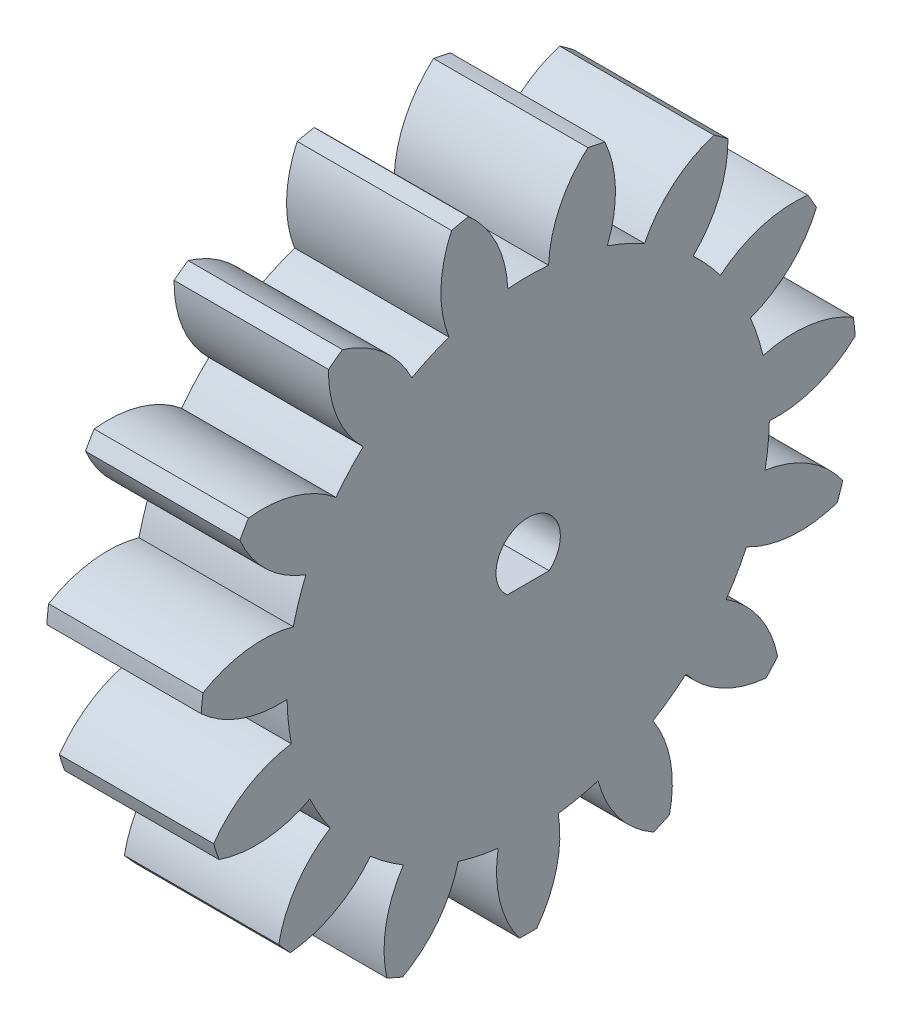
SolidWorks part; units mm, degrees
ref_plane "Plane1" through (0, 0, 0) normal (0, 0, 1) x (1, 0, 0)
ref_plane "Plane2" through (0, 0, 0) normal (0, 1, 0) x (1, 0, 0)
ref_plane "Plane3" through (0, 0, 0) normal (1, 0, 0) x (0, 0, -1)
other "Configuration Table"
sketch "HoldingSke" plane through (0, 0, 0) normal (0, 1, 0) x (1, 0, 0)
  line L0 (0, 0) -> (0.322, -0.0863)
  line L1 (-15, 0) -> (100, 0) construction
  line L2 (0, 0) -> (-2.1039, 2.3779)
  line L3 (0, 0) -> (-11.863, 4.5341)
  line L4 (0, 0) -> (8.3417, 2.2352)
  line L5 (0, 0) -> (-46.8476, -17.4728)
  line L6 (0, 0) -> (-9.9476, -6.7116)
  line L7 (-2.1039, 2.3779) -> (8.6586, 51.2059)
  line L8 (-76.2, 54.61) -> (-76.1, 54.61)
  line L9 (-71.009, 38.7566) -> (-53.1078, 45.2721)
  line L10 (-76.2, 71.12) -> (104.1128, 71.12)
  line L11 (0, 0) -> (-12, 0)
  line L12 (-76.2, 101.6) -> (-76.093, 101.6)
  line L13 (24.9733, 27.94) -> (52.9518, 28.4284)
  line L14 (24.9733, 27.94) -> (24.9743, 27.94)
  line L15 (24.9733, 27.94) -> (100.4006, 29.5858)
  line L16 (-63.627, -3) -> (-12.827, -3)
  circle A0 centre (0, 0) radius 0.4
  circle A1 centre (0, 0) radius 18.749
  circle A2 centre (0, 0) radius 37.5
  circle A3 centre (0, 0) radius 0.4
  dimension "MHD" = 37.498
  dimension "Hub_dia" = 75
  dimension "Bore" = 0.8
  dimension "MBD" = 0.8
  dimension "Num_teeth" = 15
  dimension "Pitch" = 0.3333
  dimension "Overall_len" = 50
  dimension "Show_teeth" = 15
  dimension "Thickness" = 12
  dimension "OAL" = 50.0001
  dimension "T_dim" = 0.1
  dimension "Ap" = 20
  dimension "H" = 19.05
  dimension "Pitch_radius" = 180.3128
  dimension "Width" = 12
  dimension "Backlash" = 0.107
  dimension "Addendum_fac" = 1
  dimension "Dedendum_fac" = 1.25
  dimension "Clearance_fac" = 0.25
  dimension "Dedendum_add" = 0.001
  dimension "Module" = 3
sketch "BasProSke" plane through (0, 0, 0) normal (0, 1, 0) x (1, 0, 0)
  line L0 (-10, 0) -> (60, 0) construction
  line L1 (0, 0) -> (0, 25.5)
  line L2 (0, 0) -> (12, 0)
  line L3 (12, 0) -> (12, 25.5)
  line L4 (12, 25.5) -> (0, 25.5)
  dimension "Thickness" = 12
  dimension "Diameter" = 51
revolve "Base-Revolve" add sketch "BasProSke" angle 360 about L0
sketch "TooCutSke" plane through (0, 0, 0) normal (1, 0, 0) x (0, 0, -1)
  line L1 (0, 0) -> (0, 107) construction
  line L2 (0, 0) -> (-2.539, 22.3563) construction
  line L3 (0, 0) -> (-9.3126, 43.8125) construction
  line L4 (-2.539, 22.3563) -> (-4.6563, 21.9062) construction
  arc A0 (1.5846, 18.6819) -> (-1.5846, 18.6819) centre (0, 0) ccw
  arc A1 (4.6669, 25.0951) -> (-4.6669, 25.0951) centre (0, 0) ccw
  circle A2 centre (0, 0) radius 22.5 construction
  circle A3 centre (0, 0) radius 21.1431 construction
  arc A4 (-1.5846, 18.6819) -> (-4.6669, 25.0951) centre (-10.5768, 18.3074) ccw
  arc A5 (4.6669, 25.0951) -> (1.5846, 18.6819) centre (10.5768, 18.3074) ccw
  dimension "Root_dia" = 37.498
  dimension "Overcut_dia" = 51.0508
  dimension "Pitch_dia" = 45
  dimension "Base_dia" = 42.2862
  dimension "Flank_rad" = 9
  dimension "Half_ang" = 12
  dimension "Half_CT" = 2.1646
extrude "ToothCut" cut sketch "TooCutSke" along normal through all
fillet "Breaks" [suppressed] radius 0.06
fillet "RootFillets" [suppressed] radius 0.751
pattern_circular "TeethCuts" count 15 every 24 about axis through (-10, 0, 0) along (1, 0, 0) of "ToothCut", "RootFillets", "Breaks"
sketch "HubNeaOneSke" plane through (0, 0, 0) normal (-1, 0, 0) x (0, 0, 1)
  circle A0 centre (0, 0) radius 18.749
  dimension "Diameter" = 37.498
extrude "HubNearOne" [suppressed] add sketch "HubNeaOneSke" along normal blind 38.0001
sketch "HubNeaBotSke" plane through (0, 0, 0) normal (-1, 0, 0) x (0, 0, 1)
  circle A0 centre (0, 0) radius 18.749
  dimension "Diameter" = 37.498
extrude "HubNearBoth" [suppressed] add sketch "HubNeaBotSke" along normal blind 19
ref_plane "FarPln" through (12, 0, 0) normal (1, 0, 0) x (0, 0, -1)
sketch "HubFarSke" plane through (12, 0, 0) normal (1, 0, 0) x (0, 0, -1)
  circle A0 centre (0, 0) radius 18.749
  dimension "Diameter" = 37.498
extrude "HubFar" [suppressed] add sketch "HubFarSke" along normal blind 19
sketch "BorSke" plane through (0, 0, 0) normal (1, 0, 0) x (0, 0, -1)
  circle A0 centre (0, 0) radius 0.4
  dimension "Diameter" = 0.8
extrude "Bore" cut sketch "BorSke" along normal mid plane 100.0001
sketch "KeySke" plane through (0, 0, 0) normal (1, 0, 0) x (0, 0, -1)
  line L0 (-0.05, 0) -> (-0.05, 0.5)
  line L1 (-0.05, 0.5) -> (0.05, 0.5)
  line L2 (0.05, 0.5) -> (0.05, 0)
  line L3 (0, 0) -> (0, 34) construction
  line L4 (-0.05, 0) -> (0.05, 0)
  dimension "Offset" = 0.5
  dimension "Width" = 0.1
extrude "Keyway" [suppressed] cut sketch "KeySke" along normal mid plane 100.0001
pattern_circular "Keyway2" [suppressed] count 2 every 90 about axis through (-10, 0, 0) along (1, 0, 0)
sketch "Sketch1" plane through (12, 0, 0) normal (1, 0, 0) x (0, 0, -1)
  line L0 (-3.7168, 2.5) -> (6.744, 2.5) construction
  line L1 (-4.4327, -1.9) -> (4.1469, -1.9)
  circle A0 centre (0, 0) radius 2.5
  dimension "D1" = 5
  dimension "D2" = 4.4
extrude "Cut-Extrude1" cut sketch "Sketch1" against normal through all both and the other way through all contours L1 A0
equation "' \"Module@HoldingSke\" = 6.35"
equation "' \"Num_teeth@HoldingSke\" = 12"
equation "' \"Ap@HoldingSke\" =  20"
equation "' \"Ap@HoldingSke\" = 20"
equation "' \"Width@HoldingSke\" = 0.5 * 25.4"
equation "' \"Hub_dia@HoldingSke\"= 1 * 25.4"
equation "' \"Hub_dia@HoldingSke\" = 1 * 25.4"
equation "' \"Overall_len@HoldingSke\" = 1.0 * 25.4"
equation "' \"Bore@HoldingSke\" = 0.75 * 25.4"
equation "' \"T_dim@HoldingSke\" = 0.1 * 25.4"
equation "' \"Width@KeySke\" = 0.25 * 25.4"
equation "' \"Show_teeth@HoldingSke\" = 13"
equation "' \"Backlash@HoldingSke\" = 0.009 * 25.4"
equation "' \"Addendum_fac@HoldingSke\" = 1.0"
equation "' \"Dedendum_fac@HoldingSke\" = 1.25"
equation "' \"Dedendum_add@HoldingSke\" = 0.00005 * 25.4"
equation "' \"Clearance_fac@HoldingSke\" = 0.25"
equation "\"Pitch@HoldingSke\" = 1 / \"Module@HoldingSke\""
equation "\"Overcut_dia@TooCutSke\" = (\"Num_teeth@HoldingSke\" + 2 * \"Addendum_fac@HoldingSke\") / \"Pitch@HoldingSke\" + 0.002 * 25.4"
equation "\"Pitch_dia@TooCutSke\" = \"Num_teeth@HoldingSke\" / \"Pitch@HoldingSke\""
equation "\"Base_dia@TooCutSke\" = \"Num_teeth@HoldingSke\" / \"Pitch@HoldingSke\" * cos((\"Ap@HoldingSke\"  * 3.14159265 / 180))"
equation "\"Root_dia@TooCutSke\" = (\"Num_teeth@HoldingSke\" + 2) / \"Pitch@HoldingSke\" - 2 * (\"Addendum_fac@HoldingSke\" + \"Dedendum_fac@HoldingSke\") / \"Pitch@HoldingSke\" - \"Dedendum_add@HoldingSke\" * 2"
equation "\"Half_ang@TooCutSke\" = 180 / \"Num_teeth@HoldingSke\""
equation "\"Half_CT@TooCutSke\" = \"Num_teeth@HoldingSke\" / \"Pitch@HoldingSke\" * sin((3.14159265 / 2 / \"Num_teeth@HoldingSke\")) / 2 - 7 * \"Backlash@HoldingSke\" / 4"
equation "\"Flank_rad@TooCutSke\" = \"Num_teeth@HoldingSke\" / \"Pitch@HoldingSke\" / 5"
equation "\"Radius@RootFillets\" = \"Clearance_fac@HoldingSke\" / \"Pitch@HoldingSke\" + \"Dedendum_add@HoldingSke\""
equation "\"Break_rad@Breaks\" = 0.02 / \"Pitch@HoldingSke\""
equation "\"Thickness@HoldingSke\" = \"Width@HoldingSke\""
equation "\"OAL@HoldingSke\" = \"Thickness@HoldingSke\""
equation "\"MHD@HoldingSke\" = (\"Num_teeth@HoldingSke\" + 2) / \"Pitch@HoldingSke\" - 2 * (\"Addendum_fac@HoldingSke\" + \"Dedendum_fac@HoldingSke\")  / \"Pitch@HoldingSke\" - \"Dedendum_add@HoldingSke\" * 2"
equation "\"MBD@HoldingSke\" = (\"Num_teeth@HoldingSke\" + 2) / \"Pitch@HoldingSke\" - 2 * (\"Addendum_fac@HoldingSke\" + \"Dedendum_fac@HoldingSke\")  / \"Pitch@HoldingSke\" - \"Dedendum_add@HoldingSke\" * 2 - 0.002 * 25.4"
equation "\"MHD@HoldingSke\" = ((sgn( \"MHD@HoldingSke\" - \"Hub_dia@HoldingSke\" )-1)*( \"MHD@HoldingSke\" - \"Hub_dia@HoldingSke\" ))/-2+ \"Hub_dia@HoldingSke\""
equation "\"MBD@HoldingSke\" = ((sgn( \"MBD@HoldingSke\" - \"Bore@HoldingSke\" )-1)*( \"MBD@HoldingSke\" - \"Bore@HoldingSke\" ))/-2+ \"Bore@HoldingSke\""
equation "\"OAL@HoldingSke\" = ((sgn( \"OAL@HoldingSke\" - \"Overall_len@HoldingSke\" )+1)*( \"OAL@HoldingSke\" - \"Overall_len@HoldingSke\" ))/2 + \"Overall_len@HoldingSke\" + 0.000002 * 25.4"
equation "\"Num_teeth@TeethCuts\" = int( \"Show_teeth@HoldingSke\" ) + 1"
equation "\"Num_teeth@TeethCuts\" = ((sgn( \"Num_teeth@TeethCuts\" - \"Num_teeth@HoldingSke\" )-1)*( \"Num_teeth@TeethCuts\" - \"Num_teeth@HoldingSke\" ))/-2+ \"Num_teeth@HoldingSke\""
equation "\"Num_teeth@TeethCuts\" = ((sgn( \"Num_teeth@TeethCuts\" - 2.0)+1)*( \"Num_teeth@TeethCuts\" - 2.0))/2 +2.0"
equation "\"Angle@TeethCuts\" = 360.0 / \"Num_teeth@HoldingSke\""
equation "\"Diameter@BasProSke\" = (\"Num_teeth@HoldingSke\" + 2 * \"Addendum_fac@HoldingSke\") / \"Pitch@HoldingSke\""
equation "\"Thickness@BasProSke\"  = \"Thickness@HoldingSke\""
equation "' \"Fillet_rad@BasProSke\" =  \"Thickness@HoldingSke\" * 0.05"
equation "' \"Fillet_rad@BasProSke\" = \"Thickness@HoldingSke\" * 0.05"
equation "\"MHD@HoldingSke\" = ((sgn( \"MHD@HoldingSke\" - \"Root_dia@TooCutSke\" )-1)*( \"MHD@HoldingSke\" - \"Root_dia@TooCutSke\" ))/-2+ \"Root_dia@TooCutSke\""
equation "\"Diameter@HubNeaOneSke\" = \"MHD@HoldingSke\""
equation "\"Length@HubNearOne\" = \"OAL@HoldingSke\" - \"Thickness@BasProSke\""
equation "\"Diameter@HubNeaBotSke\" = \"MHD@HoldingSke\""
equation "\"Length@HubNearBoth\" = ( \"OAL@HoldingSke\" - \"Thickness@BasProSke\" ) / 2.0"
equation "\"Thickness@FarPln\" = \"Thickness@BasProSke\""
equation "\"Diameter@HubFarSke\" = \"MHD@HoldingSke\""
equation "\"Length@HubFar\" = ( \"OAL@HoldingSke\" - \"Thickness@BasProSke\" ) / 2.0"
equation "\"Diameter@BorSke\" = \"MBD@HoldingSke\""
equation "\"D1@Bore\" = \"OAL@HoldingSke\" * 2.0"
equation "\"D1@Keyway\" = \"OAL@HoldingSke\" * 2.0"
equation "\"Offset@KeySke\" = \"T_dim@HoldingSke\" + \"MBD@HoldingSke\" / 2.0"
